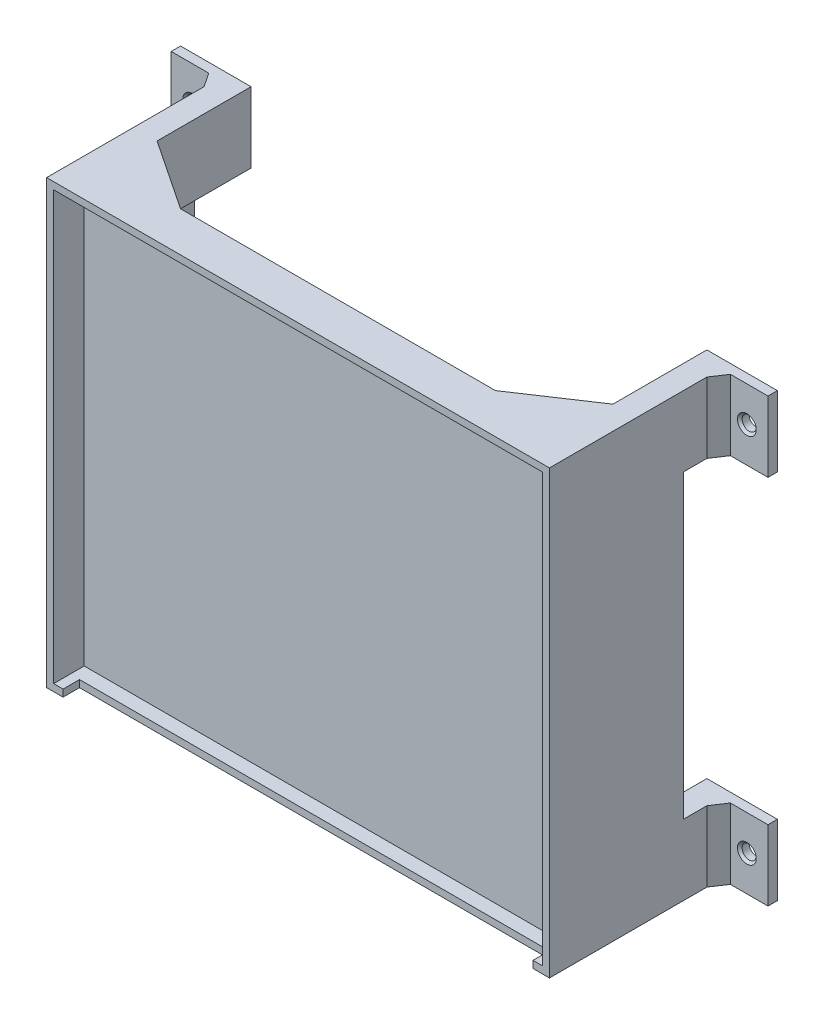
SolidWorks part; units mm, degrees
ref_plane "前视基准面" through (0, 0, 0) normal (0, 0, 1) x (1, 0, 0)
ref_plane "上视基准面" through (0, 0, 0) normal (0, 1, 0) x (1, 0, 0)
ref_plane "右视基准面" through (0, 0, 0) normal (1, 0, 0) x (0, 0, -1)
sketch "草图1" plane through (0, 0, 0) normal (0, 0, 1) x (1, 0, 0)
  line L1 (0, 0) -> (107, 0)
  line L2 (0, 0) -> (0, -94)
  line L3 (0, -94) -> (107, -94)
  line L4 (107, 0) -> (107, -94)
  dimension "D1" = 107
  dimension "D2" = 94
extrude "凸台-拉伸1" add sketch "草图1" along normal blind 2
sketch "草图2" plane through (0, 0, 2) normal (0, 0, 1) x (1, 0, 0)
  line L0 (1.5, -1.5) -> (1.5, -92.5)
  line L1 (1.5, -92.5) -> (105.5, -92.5)
  line L2 (105.5, -92.5) -> (105.5, -1.5)
  line L3 (105.5, -1.5) -> (1.5, -1.5)
  line L4 (0, 0) -> (0, -94)
  line L5 (0, -94) -> (107, -94)
  line L6 (107, -94) -> (107, 0)
  line L7 (107, 0) -> (0, 0)
  line L8 (0, 0) -> (0, -94)
  line L9 (0, -94) -> (107, -94)
  line L10 (107, -94) -> (107, 0)
  line L11 (107, 0) -> (0, 0)
  dimension "D1" = 0
  dimension "D2" = 1.5
extrude "凸台-拉伸2" add sketch "草图2" along normal blind 6.5
sketch "草图3" plane through (0, 0, 0) normal (0, 0, -1) x (-1, 0, 0)
  line L0 (-53.5, 0) -> (-53.5, 50000) construction
  line L1 (0, 0) -> (-5, 0)
  line L2 (0, 0) -> (0, -15)
  line L3 (0, -15) -> (-5, -15)
  line L4 (-5, 0) -> (-5, -15)
  line L5 (-107, 0) -> (0, 0) construction
  line L6 (0, -47) -> (50000, -47) construction
  line L7 (0, 0) -> (0, -94) construction
  line L8 (-102, 0) -> (-102, -15)
  line L9 (-107, -15) -> (-102, -15)
  line L10 (-107, 0) -> (-107, -15)
  line L11 (-107, 0) -> (-102, 0)
  line L12 (-5, -94) -> (-5, -79)
  line L13 (0, -79) -> (-5, -79)
  line L14 (0, -94) -> (0, -79)
  line L15 (0, -94) -> (-5, -94)
  line L16 (-107, -94) -> (-102, -94)
  line L17 (-107, -94) -> (-107, -79)
  line L18 (-107, -79) -> (-102, -79)
  line L19 (-102, -94) -> (-102, -79)
  point P9 (-53.5, 0)
  point P14 (0, -47)
  dimension "D1" = 5
  dimension "D2" = 15
sketch "草图5" plane through (0, -92.5, 0) normal (0, 1, 0) x (1, 0, 0)
  line L0 (1.5, -8.5) -> (105.5, -8.5) construction
  line L1 (3.5, -8.5) -> (103.5, -8.5)
  line L2 (3.5, -8.5) -> (3.5, -5)
  line L3 (3.5, -5) -> (103.5, -5)
  line L4 (103.5, -8.5) -> (103.5, -5)
  line L5 (105.5, -8.5) -> (105.5, -2) construction
  line L6 (1.5, -8.5) -> (1.5, -2) construction
  line L7 (1.5, -2) -> (105.5, -2) construction
  dimension "D1" = 2
  dimension "D2" = 2
  dimension "D3" = 3
extrude "切除-拉伸2" cut sketch "草图5" against normal blind 1.5
extrude "凸台-拉伸3" add sketch "草图3" along normal blind 30
sketch "草图6" plane through (0, 0, -30) normal (0, 0, -1) x (-1, 0, 0)
  line L0 (-102, -15) -> (-102, 0) construction
  line L1 (-102, -3) -> (-105, -3)
  line L2 (-102, -3) -> (-102, -12)
  line L3 (-102, -12) -> (-105, -12)
  line L4 (-105, -3) -> (-105, -12)
  line L5 (-107, -47) -> (49893, -47) construction
  line L6 (-107, -79) -> (-107, -15) construction
  line L7 (-53.5, 0) -> (-53.5, -50000) construction
  line L8 (-102, 0) -> (-5, 0) construction
  line L9 (-107, -15) -> (-102, -15) construction
  line L10 (-102, 0) -> (-107, 0) construction
  line L11 (-107, 0) -> (-107, -15) construction
  line L12 (-105, -91) -> (-105, -82)
  line L13 (-102, -82) -> (-105, -82)
  line L14 (-102, -91) -> (-102, -82)
  line L15 (-102, -91) -> (-105, -91)
  line L16 (-5, -91) -> (-2, -91)
  line L17 (-5, -91) -> (-5, -82)
  line L18 (-5, -82) -> (-2, -82)
  line L19 (-2, -91) -> (-2, -82)
  line L20 (-2, -3) -> (-2, -12)
  line L21 (-5, -12) -> (-2, -12)
  line L22 (-5, -3) -> (-5, -12)
  line L23 (-5, -3) -> (-2, -3)
  point P10 (-107, -47)
  point P15 (-53.5, 0)
  dimension "D1" = 3
  dimension "D2" = 3
  dimension "D3" = 2
extrude "切除-拉伸3" cut sketch "草图6" against normal up to surface (30 mm away) and the other way through all up to face at (53.5, -47, 0)
sketch "草图7" plane through (0, 0, -30) normal (0, 0, -1) x (-1, 0, 0)
  line L0 (-5, -15) -> (0, -15) construction
  line L1 (0, 0) -> (10, 0)
  line L2 (0, 0) -> (0, -15)
  line L3 (0, -15) -> (10, -15)
  line L4 (10, 0) -> (10, -15)
  line L5 (-107, -47) -> (49893, -47) construction
  line L6 (-107, -79) -> (-107, -15) construction
  line L7 (-53.5, 0) -> (-53.5, -50000) construction
  line L8 (-102, 0) -> (-5, 0) construction
  line L9 (10, -94) -> (10, -79)
  line L10 (0, -79) -> (10, -79)
  line L11 (0, -94) -> (0, -79)
  line L12 (0, -94) -> (10, -94)
  line L13 (-117, 0) -> (-117, -15)
  line L14 (-107, -15) -> (-117, -15)
  line L15 (-107, 0) -> (-107, -15)
  line L16 (-107, 0) -> (-117, 0)
  line L17 (-107, -94) -> (-117, -94)
  line L18 (-107, -94) -> (-107, -79)
  line L19 (-107, -79) -> (-117, -79)
  line L20 (-117, -94) -> (-117, -79)
  point P11 (-107, -47)
  point P16 (-53.5, 0)
  dimension "D1" = 10
extrude "凸台-拉伸4" add sketch "草图7" against normal blind 2
sketch "草图8" plane through (0, 0, -28) normal (0, 0, 1) x (1, 0, 0)
  line L0 (117, 0) -> (117, -15) construction
  line L1 (107, 0) -> (117, 0) construction
  line L2 (53.5, 0) -> (53.5, -50000) construction
  line L3 (107, 0) -> (0, 0) construction
  line L4 (1.5, -47) -> (50001.5, -47) construction
  line L5 (1.5, -1.5) -> (1.5, -92.5) construction
  circle A0 centre (112.5, -7.5) radius 1.5
  circle A1 centre (112.5, -86.5) radius 1.5
  circle A2 centre (-5.5, -7.5) radius 1.5
  circle A3 centre (-5.5, -86.5) radius 1.5
  point P10 (53.5, 0)
  point P15 (1.5, -47)
  dimension "D1" = 3
  dimension "D2" = 4.5
  dimension "D3" = 7.5
extrude "切除-拉伸4" cut sketch "草图8" against normal blind 2
chamfer "倒角1" distance 0.5 angle 45 4 edges at (111, -86.5, -28) (114, -7.5, -28) (-4, -86.5, -28) (-7, -7.5, -28)
sketch "草图9" plane through (0, -94, 0) normal (0, -1, 0) x (1, 0, 0)
  line L0 (87, 0) -> (102, -10)
  line L1 (5, 0) -> (102, 0) construction
  line L2 (102, -30) -> (102, 0) construction
  line L3 (102, -10) -> (102, 0)
  line L4 (102, 0) -> (87, 0)
  line L5 (53.5, 8.5) -> (53.5, 50008.5) construction
  line L6 (105.5, 8.5) -> (1.5, 8.5) construction
  line L7 (5, 0) -> (20, 0)
  line L8 (5, -10) -> (5, 0)
  line L9 (20, 0) -> (5, -10)
  point P12 (53.5, 8.5)
  dimension "D1" = 10
  dimension "D2" = 15
extrude "凸台-拉伸5" add sketch "草图9" against normal blind 3
sketch "草图10" plane through (0, -79, 0) normal (0, 1, 0) x (1, 0, 0)
  line L0 (102, 10) -> (87, 0)
  line L1 (87, 0) -> (102, 0)
  line L2 (102, 0) -> (102, 10)
  line L3 (53.5, 0) -> (53.5, 50000) construction
  line L4 (102, 0) -> (5, 0) construction
  line L15 (5, 0) -> (5, 10)
  line L16 (20, 0) -> (5, 0)
  line L17 (5, 10) -> (20, 0)
  point P7 (53.5, 0)
extrude "凸台-拉伸6" add sketch "草图10" against normal blind 3
sketch "草图11" plane through (0, 0, 0) normal (-1, 0, 0) x (0, 0, 1)
  line L0 (-20, -79) -> (0, -69)
  line L1 (0, -15) -> (0, -79) construction
  line L2 (0, -69) -> (0, -79)
  line L3 (0, -79) -> (-20, -79)
  dimension "D1" = 10
  dimension "D2" = 20
extrude "凸台-拉伸7" add sketch "草图11" against normal blind 3
ref_plane "基准面1" through (53.5, 0, 0) normal (1, 0, 0) x (0, 0, -1)
mirror "镜向1" about plane through (53.5, 0, 0) normal (1, 0, 0) of "凸台-拉伸7"
ref_plane "基准面2" through (0, -47, 0) normal (0, 1, 0) x (1, 0, 0)
mirror "镜向2" about plane through (0, -47, 0) normal (0, 1, 0) of "凸台-拉伸7", "凸台-拉伸6", "凸台-拉伸5", "镜向1"
sketch "草图12" plane through (0, 0, 0) normal (0, 1, 0) x (1, 0, 0)
  line L0 (107, 25) -> (109, 28)
  line L1 (107, -8.5) -> (107, 28) construction
  line L2 (107, 28) -> (117, 28) construction
  line L3 (109, 28) -> (107, 28)
  line L4 (107, 28) -> (107, 25)
  dimension "D1" = 2
  dimension "D2" = 3
extrude "凸台-拉伸8" add sketch "草图12" against normal blind 15
sketch "草图13" plane through (0, -94, 0) normal (0, -1, 0) x (1, 0, 0)
  line L3 (109, -28) -> (107, -25)
  line L4 (107, -28) -> (109, -28)
  line L5 (107, -25) -> (107, -28)
  line L6 (109, -28) -> (107, -25)
  line L7 (107, -28) -> (109, -28)
  line L8 (107, -25) -> (107, -28)
  dimension "D1" = 0
extrude "凸台-拉伸9" add sketch "草图13" against normal blind 15
mirror "镜向3" about plane through (53.5, 0, 0) normal (1, 0, 0) of "凸台-拉伸8", "凸台-拉伸9"
sketch "草图14" plane through (0, -91, 0) normal (0, 1, 0) x (1, 0, 0)
  line L5 (2, 30) -> (2, 0)
  line L6 (2, 0) -> (20, 0)
  line L7 (20, 0) -> (5, 10)
  line L8 (5, 10) -> (5, 30)
  line L9 (5, 30) -> (2, 30)
  line L10 (2, 30) -> (2, 0)
  line L11 (2, 0) -> (20, 0)
  line L12 (20, 0) -> (5, 10)
  line L13 (5, 10) -> (5, 30)
  line L14 (5, 30) -> (2, 30)
  line L15 (102, 30) -> (102, 10)
  line L16 (102, 10) -> (87, 0)
  line L17 (87, 0) -> (105, 0)
  line L18 (105, 0) -> (105, 30)
  line L19 (105, 30) -> (102, 30)
  line L20 (102, 30) -> (102, 10)
  line L21 (102, 10) -> (87, 0)
  line L22 (87, 0) -> (105, 0)
  line L23 (105, 0) -> (105, 30)
  line L24 (105, 30) -> (102, 30)
  dimension "D1" = 0
  dimension "D2" = 0
extrude "凸台-拉伸10" add sketch "草图14" along normal blind 9
sketch "草图15" plane through (0, -3, 0) normal (0, -1, 0) x (1, 0, 0)
  line L5 (105, -30) -> (105, 0)
  line L6 (105, 0) -> (87, 0)
  line L7 (87, 0) -> (102, -10)
  line L8 (102, -10) -> (102, -30)
  line L9 (102, -30) -> (105, -30)
  line L10 (105, -30) -> (105, 0)
  line L11 (105, 0) -> (87, 0)
  line L13 (102, -10) -> (102, -30)
  line L14 (102, -30) -> (105, -30)
  line L15 (5, -30) -> (5, -10)
  line L16 (87, 0) -> (102, -10)
  line L17 (20, 0) -> (2, 0)
  line L18 (2, 0) -> (2, -30)
  line L19 (2, -30) -> (5, -30)
  line L20 (5, -30) -> (5, -10)
  line L22 (20, 0) -> (2, 0)
  line L23 (2, 0) -> (2, -30)
  line L24 (2, -30) -> (5, -30)
  line L25 (5, -10) -> (20, 0)
  line L26 (5, -10) -> (20, 0)
  dimension "D1" = 0
  dimension "D2" = 0
extrude "凸台-拉伸11" add sketch "草图15" along normal blind 9
sketch "草图17" plane through (0, 0, 0) normal (-1, 0, 0) x (0, 0, 1)
  line L0 (-20, -15) -> (-20, -79)
  line L1 (-20, -79) -> (0, -69)
  line L2 (0, -69) -> (0, -25)
  line L3 (0, -25) -> (-20, -15)
extrude "凸台-拉伸12" add sketch "草图17" against normal blind 3
mirror "镜向4" about plane through (53.5, 0, 0) normal (1, 0, 0) of "凸台-拉伸12"
